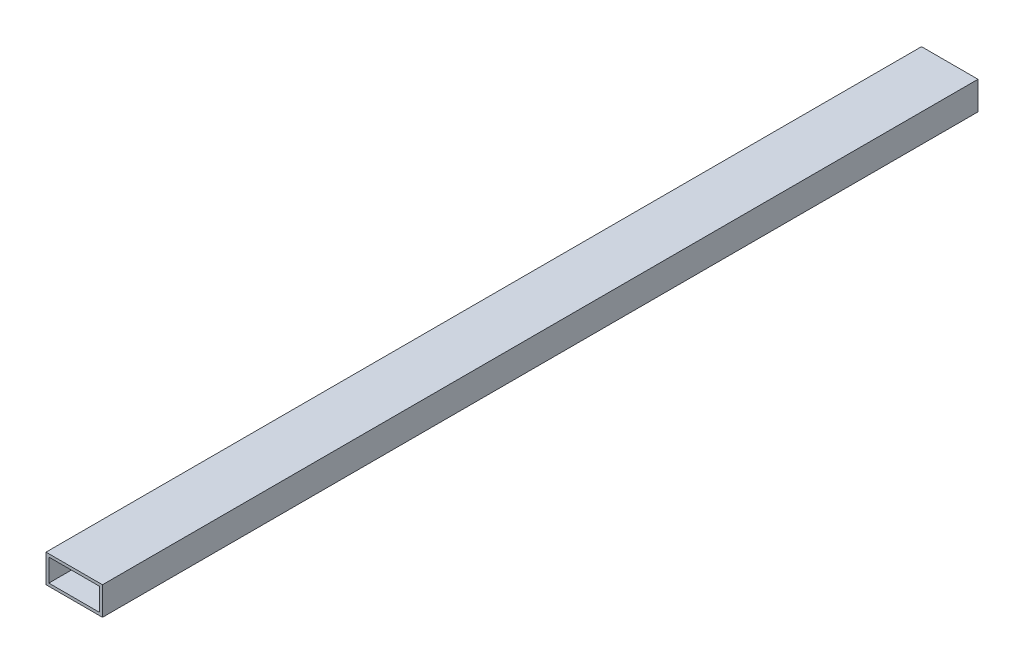
SolidWorks part; units mm, degrees
ref_plane "Спереди" through (0, 0, 0) normal (0, 0, 1) x (1, 0, 0)
ref_plane "Сверху" through (0, 0, 0) normal (0, 1, 0) x (1, 0, 0)
ref_plane "Справа" through (0, 0, 0) normal (1, 0, 0) x (0, 0, -1)
sketch "Эскиз1" plane through (0, 0, 0) normal (0, 0, 1) x (1, 0, 0)
  line L1 (-44.3827, 11.1114) -> (-4.3827, 11.1114)
  line L2 (-44.3827, 11.1114) -> (-44.3827, -8.8886)
  line L3 (-44.3827, -8.8886) -> (-4.3827, -8.8886)
  line L4 (-4.3827, 11.1114) -> (-4.3827, -8.8886)
  line L5 (-42.3827, 9.1114) -> (-6.3827, 9.1114)
  line L6 (-42.3827, 9.1114) -> (-42.3827, -6.8886)
  line L7 (-42.3827, -6.8886) -> (-6.3827, -6.8886)
  line L8 (-6.3827, 9.1114) -> (-6.3827, -6.8886)
  dimension "D1" = 40
  dimension "D2" = 20
  dimension "D3" = 2
  dimension "D4" = 2
  dimension "D5" = 2
  dimension "D6" = 2
extrude "Бобышка-Вытянуть1" add sketch "Эскиз1" along normal blind 620
